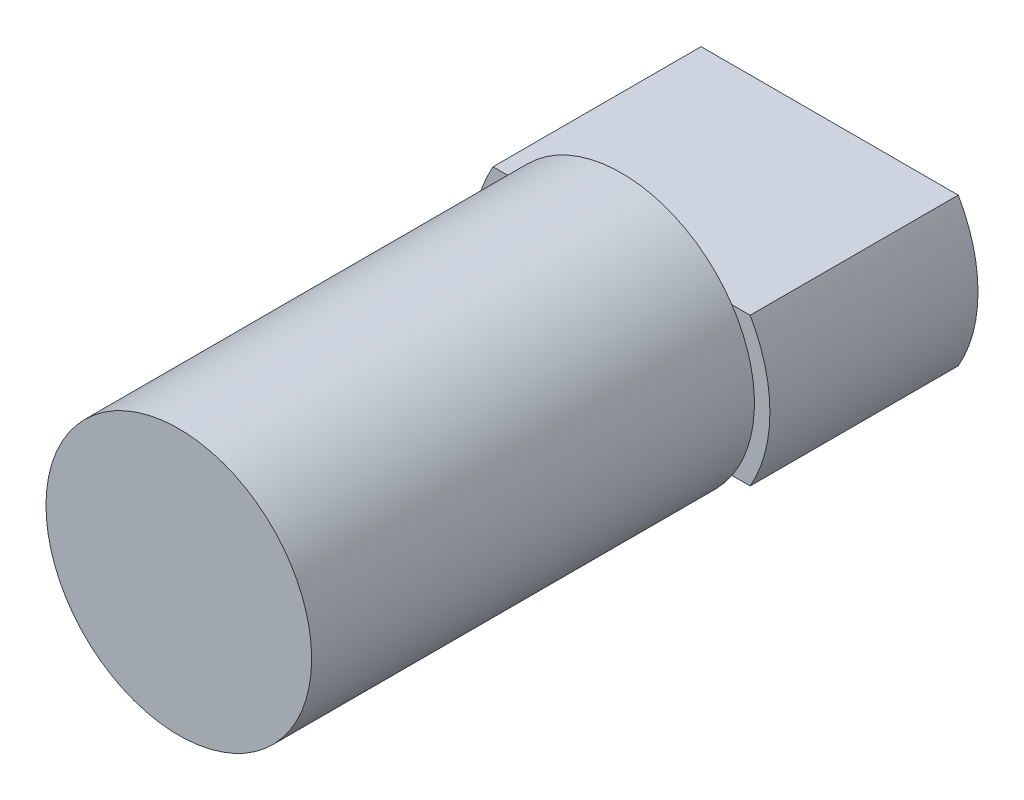
SolidWorks part; units mm, degrees
ref_plane "前视基准面" through (0, 0, 0) normal (0, 0, 1) x (1, 0, 0)
ref_plane "上视基准面" through (0, 0, 0) normal (0, 1, 0) x (1, 0, 0)
ref_plane "右视基准面" through (0, 0, 0) normal (1, 0, 0) x (0, 0, -1)
other "Configuration Table"
sketch "草图1" plane through (0, 0, 0) normal (0, 0, 1) x (1, 0, 0)
  line L1 (-14.5203, -8.35) -> (14.5203, -8.35)
  line L2 (-14.5203, -8.35) -> (-14.5203, 8.35)
  line L3 (-14.5203, 8.35) -> (14.5203, 8.35)
  line L4 (14.5203, -8.35) -> (14.5203, 8.35)
  line L5 (0, 8.35) -> (0, -8.35) construction
  line L6 (-14.5203, 0) -> (14.5203, 0) construction
  arc A0 (-14.5203, 8.35) -> (-14.5203, -8.35) centre (0, 0) ccw
  arc A1 (14.5203, -8.35) -> (14.5203, 8.35) centre (0, 0) ccw
  dimension "D1" = 33.5
  dimension "D2" = 16.7
extrude "凸台-拉伸3" add sketch "草图1" against normal blind 23.5 contours L1 L4 L3 L2 | L2 A0 | L4 A1
sketch "草图3" plane through (0, 0, 0) normal (0, 0, 1) x (1, 0, 0)
  circle A0 centre (0, 0) radius 15
  dimension "D1" = 30
extrude "凸台-拉伸4" add sketch "草图3" along normal blind 50
